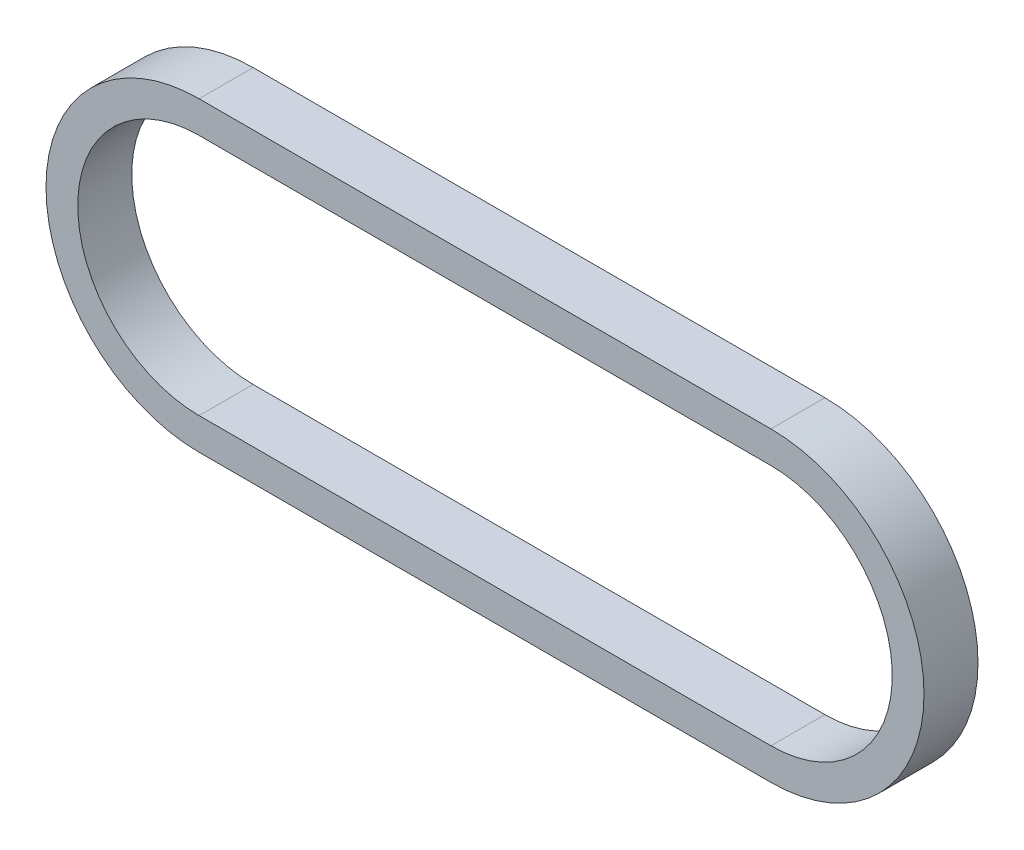
SolidWorks part; units mm, degrees
ref_plane "Front Plane" through (0, 0, 0) normal (0, 0, 1) x (1, 0, 0)
ref_plane "Top Plane" through (0, 0, 0) normal (0, 1, 0) x (1, 0, 0)
ref_plane "Right Plane" through (0, 0, 0) normal (1, 0, 0) x (0, 0, -1)
sketch "Sketch1" plane through (0, 0, 0) normal (0, 0, 1) x (1, 0, 0)
  line L0 (-45.0126, 0) -> (45.0126, 0) construction
  line L1 (-45.0126, 19.1008) -> (45.0126, 19.1008)
  line L2 (-45.0126, -19.1008) -> (45.0126, -19.1008)
  circle A0 centre (-45.0126, 0) radius 19.1008 construction
  circle A1 centre (45.0126, 0) radius 19.1008 construction
  arc A2 (-45.0126, -19.1008) -> (-45.0126, 19.1008) centre (-45.0126, 0) cw
  arc A3 (45.0126, -19.1008) -> (45.0126, 19.1008) centre (45.0126, 0) ccw
  dimension "D1" = 38.2016
  dimension "D2" = 90.0252
extrude "Extrude-Thin1" add sketch "Sketch1" along normal mid plane 8.5 thin thin type one direction wall 5
